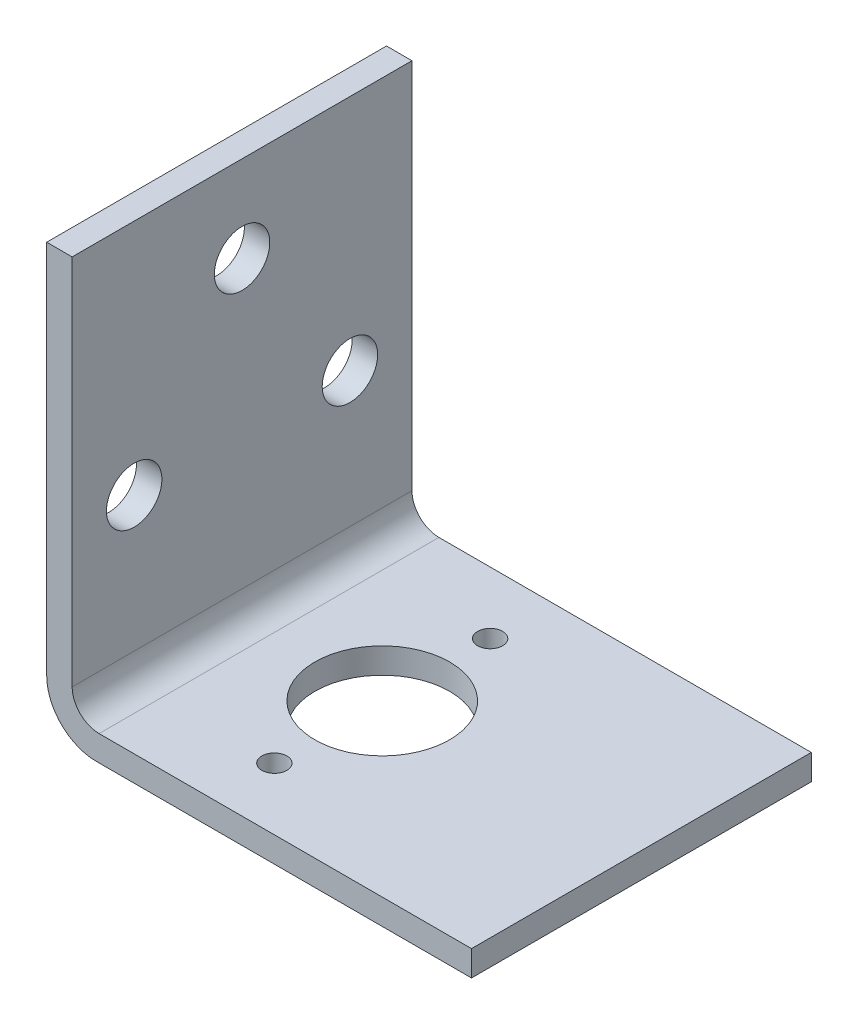
SolidWorks part; units mm, degrees
ref_plane "Front" through (0, 0, 0) normal (0, 0, 1) x (1, 0, 0)
ref_plane "Top" through (0, 0, 0) normal (0, 1, 0) x (1, 0, 0)
ref_plane "Right" through (0, 0, 0) normal (1, 0, 0) x (0, 0, -1)
sketch "Sketch2" plane through (0, 0, 0) normal (0, 0, 1) x (1, 0, 0)
  line L0 (0, 5.842) -> (0, 50.0126)
  line L1 (5.842, 0) -> (50.0126, 0)
  line L2 (6.1722, 2.9972) -> (50.0126, 2.9972)
  line L3 (2.9972, 6.1722) -> (2.9972, 50.0126)
  line L4 (0, 50.0126) -> (2.9972, 50.0126)
  line L5 (50.0126, 2.9972) -> (50.0126, 0)
  line L6 (2.9972, 2.9972) -> (50.0126, 2.9972) construction
  line L7 (2.9972, 2.9972) -> (2.9972, 50.0126) construction
  line L8 (0, 0) -> (0, 50.0126) construction
  line L9 (0, 0) -> (50.0126, 0) construction
  arc A0 (6.1722, 2.9972) -> (2.9972, 6.1722) centre (6.1722, 6.1722) cw
  arc A1 (0, 5.842) -> (5.842, 0) centre (5.842, 5.842) ccw
  point P13 (0, 0)
  dimension "D4" = 3.175
  dimension "D5" = 5.842
  dimension "D2" = 50.0126
  dimension "D3" = 50.0126
  dimension "D1" = 2.9972
extrude "Boss-Extrude1" add sketch "Sketch2" along normal blind 40.005
sketch "Sketch3" plane through (0, 0, 0) normal (0, -1, 0) x (1, 0, 0)
  line L0 (50.0126, 20.0025) -> (5.842, 20.0025) construction
  line L1 (50.0126, 40.005) -> (50.0126, 0) construction
  line L2 (5.842, 40.005) -> (5.842, 0) construction
  line L3 (0, 40.005) -> (0, 0) construction
  circle A0 centre (19.5, 32.7025) radius 1.4732
  circle A1 centre (19.5, 7.3025) radius 1.4732
  circle A2 centre (19.5, 20.0025) radius 7.9375
  dimension "D1" = 2.9464
  dimension "D4" = 15.875
  dimension "D2" = 25.4
  dimension "D3" = 19.5
extrude "4-40 For Nut Vertical" cut sketch "Sketch3" against normal through all and the other way through all
sketch "Sketch4" plane through (0, 0, 0) normal (-1, 0, 0) x (0, 0, 1)
  line L0 (7.3025, 22.0726) -> (32.7025, 22.0726) construction
  line L2 (40.005, 50.0126) -> (0, 50.0126) construction
  circle A0 centre (7.3025, 22.0726) radius 3.2639
  circle A1 centre (32.7025, 22.0726) radius 3.2639
  circle A2 centre (20.0025, 39.8526) radius 3.2639
  point P4 (20.0025, 50.0126)
  point P5 (20.0025, 22.0726)
  dimension "D1" = 25.4
  dimension "D2" = 6.5278
  dimension "D4" = 17.78
  dimension "D3" = 27.94
extrude "1/4-20 Mounting" cut sketch "Sketch4" against normal through all
equation "\"D5@Sketch2\"=\"D4@Sketch2\"+.105"
